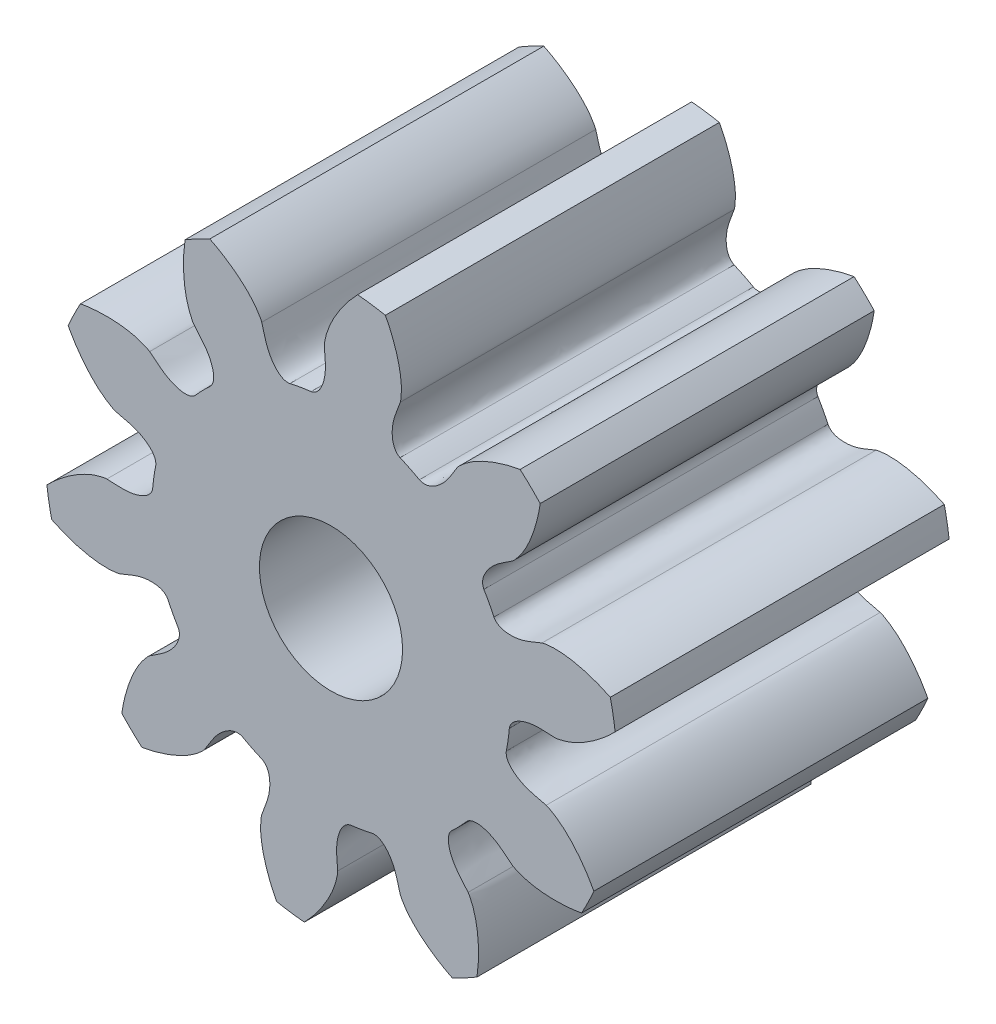
SolidWorks part; units mm, degrees
ref_plane "Plan de face" through (0, 0, 0) normal (0, 0, 1) x (1, 0, 0)
ref_plane "Plan de dessus" through (0, 0, 0) normal (0, 1, 0) x (1, 0, 0)
ref_plane "Plan de droite" through (0, 0, 0) normal (1, 0, 0) x (0, 0, -1)
sketch "Esquisse1" plane through (0, 0, 0) normal (0, 0, 1) x (1, 0, 0)
  arc A0 (2.9773, 0.3683) -> (2.9271, 0.6573) centre (0, 0) ccw
  arc A1 (2.1922, 2.048) -> (1.9817, 2.2523) centre (0, 0) ccw
  arc A2 (0.5698, 2.9454) -> (0.2794, 2.987) centre (0, 0) ccw
  arc A3 (-1.2703, 2.7178) -> (-1.5297, 2.5807) centre (0, 0) ccw
  arc A4 (-2.6252, 1.4521) -> (-2.7544, 1.1887) centre (0, 0) ccw
  arc A5 (-2.9773, -0.3683) -> (-2.9271, -0.6573) centre (0, 0) ccw
  arc A6 (-2.1922, -2.048) -> (-1.9817, -2.2523) centre (0, 0) ccw
  arc A7 (-0.5698, -2.9454) -> (-0.2794, -2.987) centre (0, 0) ccw
  arc A8 (1.2703, -2.7178) -> (1.5297, -2.5807) centre (0, 0) ccw
  arc A9 (2.6252, -1.4521) -> (2.7544, -1.1887) centre (0, 0) ccw
  arc A10 (1.8368, -0.3764) -> (1.8687, -0.154) centre (0, 0) ccw
  arc A11 (1.7073, 0.7751) -> (1.6023, 0.9738) centre (0, 0) ccw
  arc A12 (0.9256, 1.6306) -> (0.7239, 1.7296) centre (0, 0) ccw
  arc A13 (-0.2096, 1.8632) -> (-0.431, 1.8248) centre (0, 0) ccw
  arc A14 (-1.2648, 1.3842) -> (-1.4213, 1.2229) centre (0, 0) ccw
  arc A15 (-1.8368, 0.3764) -> (-1.8687, 0.154) centre (0, 0) ccw
  arc A16 (-1.7073, -0.7751) -> (-1.6023, -0.9738) centre (0, 0) ccw
  arc A17 (-0.9256, -1.6306) -> (-0.7239, -1.7296) centre (0, 0) ccw
  arc A18 (0.2096, -1.8632) -> (0.431, -1.8248) centre (0, 0) ccw
  arc A19 (1.2648, -1.3842) -> (1.4213, -1.2229) centre (0, 0) ccw
  circle A20 centre (0, 0) radius 0.75
  spline S0 degree 3 poles (2.349, 0) (2.3611, 0) (2.4126, 0.0085) (2.4945, 0.0326) (2.6584, 0.1065) (2.823, 0.2207) (2.9394, 0.3292) (2.9773, 0.3683) knots 0 0 0 0 0.036251 0.155621 0.255291 0.575255 0.744085 0.744085 0.744085 0.744085
  spline S1 degree 3 poles (2.2114, 0.7921) (2.2228, 0.7962) (2.2741, 0.8056) (2.3594, 0.8105) (2.5386, 0.7962) (2.7321, 0.7442) (2.8782, 0.6813) (2.9271, 0.6573) knots 0 0 0 0 0.036251 0.155621 0.255291 0.575255 0.744085 0.744085 0.744085 0.744085
  spline S2 degree 3 poles (1.9004, 1.3807) (1.9102, 1.3878) (1.9469, 1.4249) (1.9989, 1.4926) (2.0881, 1.6487) (2.1541, 1.8379) (2.1845, 1.9941) (2.1922, 2.048) knots 0 0 0 0 0.036251 0.155621 0.255291 0.575255 0.744085 0.744085 0.744085 0.744085
  spline S3 degree 3 poles (1.3235, 1.9407) (1.3303, 1.9507) (1.3663, 1.9885) (1.4324, 2.0425) (1.5858, 2.1363) (1.7728, 2.2079) (1.9281, 2.243) (1.9817, 2.2523) knots 0 0 0 0 0.036251 0.155621 0.255291 0.575255 0.744085 0.744085 0.744085 0.744085
  spline S4 degree 3 poles (0.7259, 2.234) (0.7296, 2.2455) (0.7375, 2.2971) (0.7398, 2.3825) (0.7202, 2.5612) (0.6625, 2.753) (0.5952, 2.8973) (0.5698, 2.9454) knots 0 0 0 0 0.036251 0.155621 0.255291 0.575255 0.744085 0.744085 0.744085 0.744085
  spline S5 degree 3 poles (-0.07, 2.348) (-0.0704, 2.36) (-0.0634, 2.4118) (-0.0417, 2.4943) (0.0272, 2.6604) (0.1365, 2.8283) (0.2415, 2.9479) (0.2794, 2.987) knots 0 0 0 0 0.036251 0.155621 0.255291 0.575255 0.744085 0.744085 0.744085 0.744085
  spline S6 degree 3 poles (-0.7259, 2.234) (-0.7296, 2.2455) (-0.7536, 2.2919) (-0.8019, 2.3623) (-0.9228, 2.4954) (-1.0823, 2.6166) (-1.2215, 2.6938) (-1.2703, 2.7178) knots 0 0 0 0 0.036251 0.155621 0.255291 0.575255 0.744085 0.744085 0.744085 0.744085
  spline S7 degree 3 poles (-1.4367, 1.8584) (-1.4441, 1.8679) (-1.4689, 1.9139) (-1.4999, 1.9934) (-1.5417, 2.1683) (-1.552, 2.3684) (-1.5374, 2.5268) (-1.5297, 2.5807) knots 0 0 0 0 0.036251 0.155621 0.255291 0.575255 0.744085 0.744085 0.744085 0.744085
  spline S8 degree 3 poles (-1.9004, 1.3807) (-1.9102, 1.3878) (-1.9568, 1.4112) (-2.0373, 1.4398) (-2.2133, 1.4764) (-2.4136, 1.4808) (-2.5715, 1.4614) (-2.6252, 1.4521) knots 0 0 0 0 0.036251 0.155621 0.255291 0.575255 0.744085 0.744085 0.744085 0.744085
  spline S9 degree 3 poles (-2.2547, 0.659) (-2.2663, 0.6624) (-2.3133, 0.6849) (-2.3852, 0.7311) (-2.5218, 0.848) (-2.6477, 1.0038) (-2.729, 1.1406) (-2.7544, 1.1887) knots 0 0 0 0 0.036251 0.155621 0.255291 0.575255 0.744085 0.744085 0.744085 0.744085
  spline S10 degree 3 poles (-2.349, 0) (-2.3611, 0) (-2.4126, -0.0085) (-2.4945, -0.0326) (-2.6584, -0.1065) (-2.823, -0.2207) (-2.9394, -0.3292) (-2.9773, -0.3683) knots 0 0 0 0 0.036251 0.155621 0.255291 0.575255 0.744085 0.744085 0.744085 0.744085
  spline S11 degree 3 poles (-2.2114, -0.7921) (-2.2228, -0.7962) (-2.2741, -0.8056) (-2.3594, -0.8105) (-2.5386, -0.7962) (-2.7321, -0.7442) (-2.8782, -0.6813) (-2.9271, -0.6573) knots 0 0 0 0 0.036251 0.155621 0.255291 0.575255 0.744085 0.744085 0.744085 0.744085
  spline S12 degree 3 poles (-1.9004, -1.3807) (-1.9102, -1.3878) (-1.9469, -1.4249) (-1.9989, -1.4926) (-2.0881, -1.6487) (-2.1541, -1.8379) (-2.1845, -1.9941) (-2.1922, -2.048) knots 0 0 0 0 0.036251 0.155621 0.255291 0.575255 0.744085 0.744085 0.744085 0.744085
  spline S13 degree 3 poles (-1.3235, -1.9407) (-1.3303, -1.9507) (-1.3663, -1.9885) (-1.4324, -2.0425) (-1.5858, -2.1363) (-1.7728, -2.2079) (-1.9281, -2.243) (-1.9817, -2.2523) knots 0 0 0 0 0.036251 0.155621 0.255291 0.575255 0.744085 0.744085 0.744085 0.744085
  spline S14 degree 3 poles (-0.7259, -2.234) (-0.7296, -2.2455) (-0.7375, -2.2971) (-0.7398, -2.3825) (-0.7202, -2.5612) (-0.6625, -2.753) (-0.5952, -2.8973) (-0.5698, -2.9454) knots 0 0 0 0 0.036251 0.155621 0.255291 0.575255 0.744085 0.744085 0.744085 0.744085
  spline S15 degree 3 poles (0.07, -2.348) (0.0704, -2.36) (0.0634, -2.4118) (0.0417, -2.4943) (-0.0272, -2.6604) (-0.1365, -2.8283) (-0.2415, -2.9479) (-0.2794, -2.987) knots 0 0 0 0 0.036251 0.155621 0.255291 0.575255 0.744085 0.744085 0.744085 0.744085
  spline S16 degree 3 poles (0.7259, -2.234) (0.7296, -2.2455) (0.7536, -2.2919) (0.8019, -2.3623) (0.9228, -2.4954) (1.0823, -2.6166) (1.2215, -2.6938) (1.2703, -2.7178) knots 0 0 0 0 0.036251 0.155621 0.255291 0.575255 0.744085 0.744085 0.744085 0.744085
  spline S17 degree 3 poles (1.4367, -1.8584) (1.4441, -1.8679) (1.4689, -1.9139) (1.4999, -1.9934) (1.5417, -2.1683) (1.552, -2.3684) (1.5374, -2.5268) (1.5297, -2.5807) knots 0 0 0 0 0.036251 0.155621 0.255291 0.575255 0.744085 0.744085 0.744085 0.744085
  spline S18 degree 3 poles (1.9004, -1.3807) (1.9102, -1.3878) (1.9568, -1.4112) (2.0373, -1.4398) (2.2133, -1.4764) (2.4136, -1.4808) (2.5715, -1.4614) (2.6252, -1.4521) knots 0 0 0 0 0.036251 0.155621 0.255291 0.575255 0.744085 0.744085 0.744085 0.744085
  spline S19 degree 3 poles (2.2547, -0.659) (2.2663, -0.6624) (2.3133, -0.6849) (2.3852, -0.7311) (2.5218, -0.848) (2.6477, -1.0038) (2.729, -1.1406) (2.7544, -1.1887) knots 0 0 0 0 0.036251 0.155621 0.255291 0.575255 0.744085 0.744085 0.744085 0.744085
  spline S20 degree 3 poles (2.349, 0) (2.2648, 0) (2.1034, 0.0291) (1.8817, -0.0633) (1.8687, -0.154) knots 0 0 0 0 0.252618 0.527509 0.527509 0.527509 0.527509
  spline S21 degree 3 poles (2.2547, -0.659) (2.1739, -0.6353) (2.0108, -0.618) (1.8238, -0.4671) (1.8368, -0.3764) knots 0 0 0 0 0.252618 0.527509 0.527509 0.527509 0.527509
  spline S22 degree 3 poles (1.9004, 1.3807) (1.8323, 1.3312) (1.6846, 1.2599) (1.5595, 1.0548) (1.6023, 0.9738) knots 0 0 0 0 0.252618 0.527509 0.527509 0.527509 0.527509
  spline S23 degree 3 poles (2.2114, 0.7921) (2.1321, 0.7637) (1.99, 0.682) (1.7501, 0.6941) (1.7073, 0.7751) knots 0 0 0 0 0.252618 0.527509 0.527509 0.527509 0.527509
  spline S24 degree 3 poles (0.7259, 2.234) (0.6999, 2.1539) (0.6223, 2.0095) (0.6416, 1.77) (0.7239, 1.7296) knots 0 0 0 0 0.252618 0.527509 0.527509 0.527509 0.527509
  spline S25 degree 3 poles (1.3235, 1.9407) (1.276, 1.8711) (1.2091, 1.7214) (1.0079, 1.5902) (0.9256, 1.6306) knots 0 0 0 0 0.252618 0.527509 0.527509 0.527509 0.527509
  spline S26 degree 3 poles (-0.7259, 2.234) (-0.6999, 2.1539) (-0.6776, 1.9915) (-0.5213, 1.8091) (-0.431, 1.8248) knots 0 0 0 0 0.252618 0.527509 0.527509 0.527509 0.527509
  spline S27 degree 3 poles (-0.07, 2.348) (-0.0675, 2.2638) (-0.0336, 2.1034) (-0.1193, 1.8789) (-0.2096, 1.8632) knots 0 0 0 0 0.252618 0.527509 0.527509 0.527509 0.527509
  spline S28 degree 3 poles (-1.9004, 1.3807) (-1.8323, 1.3312) (-1.7188, 1.2128) (-1.4851, 1.1572) (-1.4213, 1.2229) knots 0 0 0 0 0.252618 0.527509 0.527509 0.527509 0.527509
  spline S29 degree 3 poles (-1.4367, 1.8584) (-1.3852, 1.7918) (-1.2635, 1.6819) (-1.2009, 1.4499) (-1.2648, 1.3842) knots 0 0 0 0 0.252618 0.527509 0.527509 0.527509 0.527509
  spline S30 degree 3 poles (-2.349, 0) (-2.2648, 0) (-2.1034, -0.0291) (-1.8817, 0.0633) (-1.8687, 0.154) knots 0 0 0 0 0.252618 0.527509 0.527509 0.527509 0.527509
  spline S31 degree 3 poles (-2.2547, 0.659) (-2.1739, 0.6353) (-2.0108, 0.618) (-1.8238, 0.4671) (-1.8368, 0.3764) knots 0 0 0 0 0.252618 0.527509 0.527509 0.527509 0.527509
  spline S32 degree 3 poles (-1.9004, -1.3807) (-1.8323, -1.3312) (-1.6846, -1.2599) (-1.5595, -1.0548) (-1.6023, -0.9738) knots 0 0 0 0 0.252618 0.527509 0.527509 0.527509 0.527509
  spline S33 degree 3 poles (-2.2114, -0.7921) (-2.1321, -0.7637) (-1.99, -0.682) (-1.7501, -0.6941) (-1.7073, -0.7751) knots 0 0 0 0 0.252618 0.527509 0.527509 0.527509 0.527509
  spline S34 degree 3 poles (-0.7259, -2.234) (-0.6999, -2.1539) (-0.6223, -2.0095) (-0.6416, -1.77) (-0.7239, -1.7296) knots 0 0 0 0 0.252618 0.527509 0.527509 0.527509 0.527509
  spline S35 degree 3 poles (-1.3235, -1.9407) (-1.276, -1.8711) (-1.2091, -1.7214) (-1.0079, -1.5902) (-0.9256, -1.6306) knots 0 0 0 0 0.252618 0.527509 0.527509 0.527509 0.527509
  spline S36 degree 3 poles (0.7259, -2.234) (0.6999, -2.1539) (0.6776, -1.9915) (0.5213, -1.8091) (0.431, -1.8248) knots 0 0 0 0 0.252618 0.527509 0.527509 0.527509 0.527509
  spline S37 degree 3 poles (0.07, -2.348) (0.0675, -2.2638) (0.0336, -2.1034) (0.1193, -1.8789) (0.2096, -1.8632) knots 0 0 0 0 0.252618 0.527509 0.527509 0.527509 0.527509
  spline S38 degree 3 poles (1.9004, -1.3807) (1.8323, -1.3312) (1.7188, -1.2128) (1.4851, -1.1572) (1.4213, -1.2229) knots 0 0 0 0 0.252618 0.527509 0.527509 0.527509 0.527509
  spline S39 degree 3 poles (1.4367, -1.8584) (1.3852, -1.7918) (1.2635, -1.6819) (1.2009, -1.4499) (1.2648, -1.3842) knots 0 0 0 0 0.252618 0.527509 0.527509 0.527509 0.527509
  dimension "D1" = 1.5
extrude "Boss.-Extru.1" add sketch "Esquisse1" along normal blind 3.5
